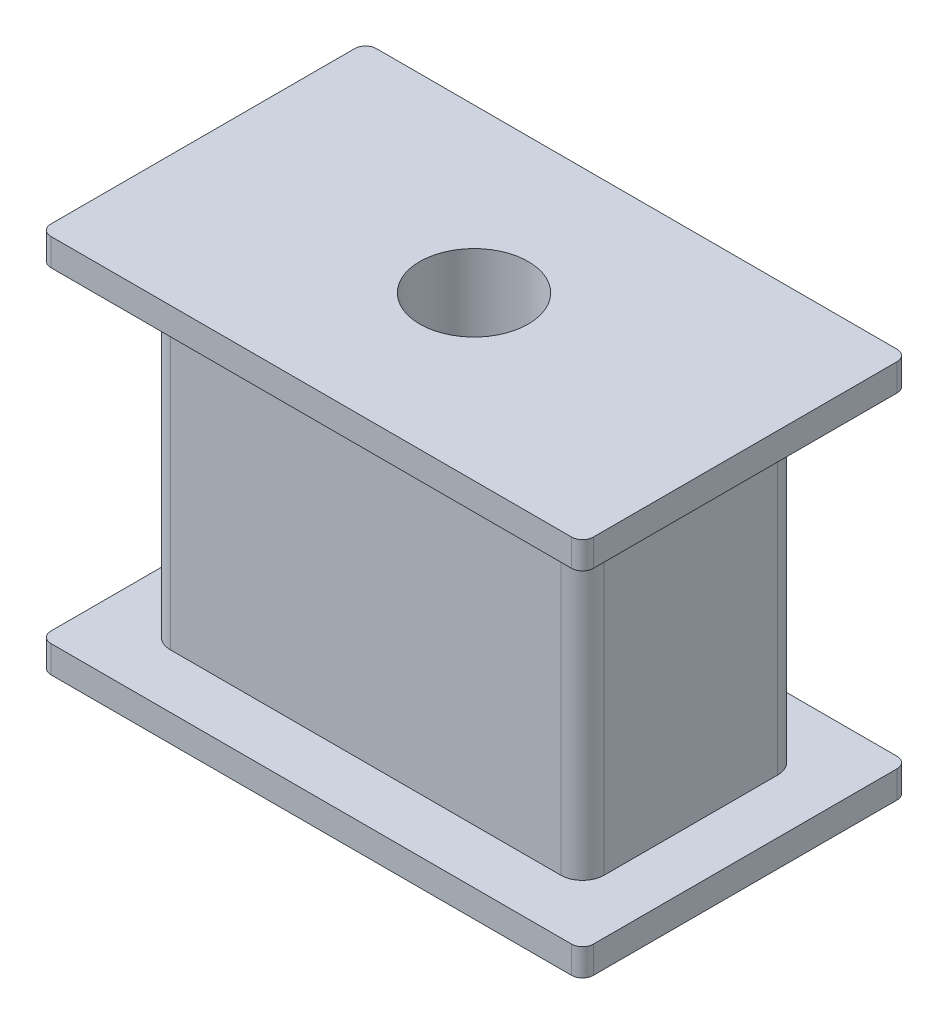
SolidWorks part; units mm, degrees
ref_plane "Front Plane" through (0, 0, 0) normal (0, 0, 1) x (1, 0, 0)
ref_plane "Top Plane" through (0, 0, 0) normal (0, 1, 0) x (1, 0, 0)
ref_plane "Right Plane" through (0, 0, 0) normal (1, 0, 0) x (0, 0, -1)
sketch "Sketch1" plane through (0, 0, 0) normal (0, 1, 0) x (1, 0, 0)
  line L1 (-20, -10) -> (20, -10)
  line L2 (-20, -10) -> (-20, 10)
  line L3 (-20, 10) -> (20, 10)
  line L4 (20, -10) -> (20, 10)
  line L5 (-20, -10) -> (20, 10) construction
  line L6 (-20, 10) -> (20, -10) construction
  point P0 (0, 0)
  dimension "D1" = 40
  dimension "D2" = 20
extrude "Main Body" add sketch "Sketch1" along normal blind 30
sketch "Sketch2" plane through (0, 30, 0) normal (0, 1, 0) x (1, 0, 0)
  line L1 (-25, -15) -> (25, -15)
  line L2 (-25, -15) -> (-25, 15)
  line L3 (-25, 15) -> (25, 15)
  line L4 (25, -15) -> (25, 15)
  line L5 (-25, -15) -> (25, 15) construction
  line L6 (-25, 15) -> (25, -15) construction
  point P0 (0, 0)
  dimension "D1" = 30
  dimension "D2" = 50
extrude "Flange 1" add sketch "Sketch2" along normal blind 2.5
sketch "Sketch4" plane through (0, 0, 0) normal (0, -1, 0) x (1, 0, 0)
  line L0 (-25, -15) -> (-25, 15) construction
  line L1 (-25, -15) -> (-25, 15)
  line L2 (25, 15) -> (25, -15) construction
  line L3 (-25, 15) -> (25, 15) construction
  line L4 (20, -10) -> (20, 10)
  line L5 (20, 10) -> (-20, 10)
  line L6 (-20, 10) -> (-20, -10)
  line L7 (-20, -10) -> (20, -10)
  line L8 (20, -10) -> (20, 10)
  line L9 (20, 10) -> (-20, 10)
  line L10 (-20, 10) -> (-20, -10)
  line L11 (-20, -10) -> (20, -10)
  line L12 (25, -15) -> (-25, -15) construction
  line L13 (25, -15) -> (-25, -15)
  line L14 (-25, 15) -> (25, 15)
  line L15 (25, 15) -> (25, -15)
  line L17 (-25, -15) -> (25, -15)
  line L18 (-25, -15) -> (-25, 15)
  line L19 (-25, 15) -> (25, 15)
  line L20 (25, -15) -> (25, 15)
  line L21 (-25, -15) -> (25, 15) construction
  line L22 (-25, 15) -> (25, -15) construction
  point P6 (0, 0)
  line M9 (20, -10) -> (20, 10)
  line M10 (20, 10) -> (-20, 10)
  line M11 (-20, 10) -> (-20, -10)
  line M12 (-20, -10) -> (20, -10)
  dimension "D1" = 0
extrude "Flange 2" add sketch "Sketch4" along normal blind 2.5 contours L15 L14 L1 L13 M9 M12 M11 M10 | L8 L9 L10 L11
sketch "Sketch5" plane through (0, 32.5, 0) normal (0, 1, 0) x (1, 0, 0)
  circle A0 centre (0, 0) radius 5
  dimension "D1" = 10
extrude "Hole" cut sketch "Sketch5" against normal through all
fillet "Main Body Fillet" radius 2 4 edges at (-20, 15, 10) (-20, 15, -10) (20, 15, 10) (20, 15, -10)
fillet "Flange Fillet" radius 1 8 edges at (25, 31.25, 15) (25, 31.25, -15) (-25, 31.25, 15) (-25, 31.25, -15) (25, -1.25, 15) (-25, -1.25, 15) (-25, -1.25, -15) (25, -1.25, -15)
